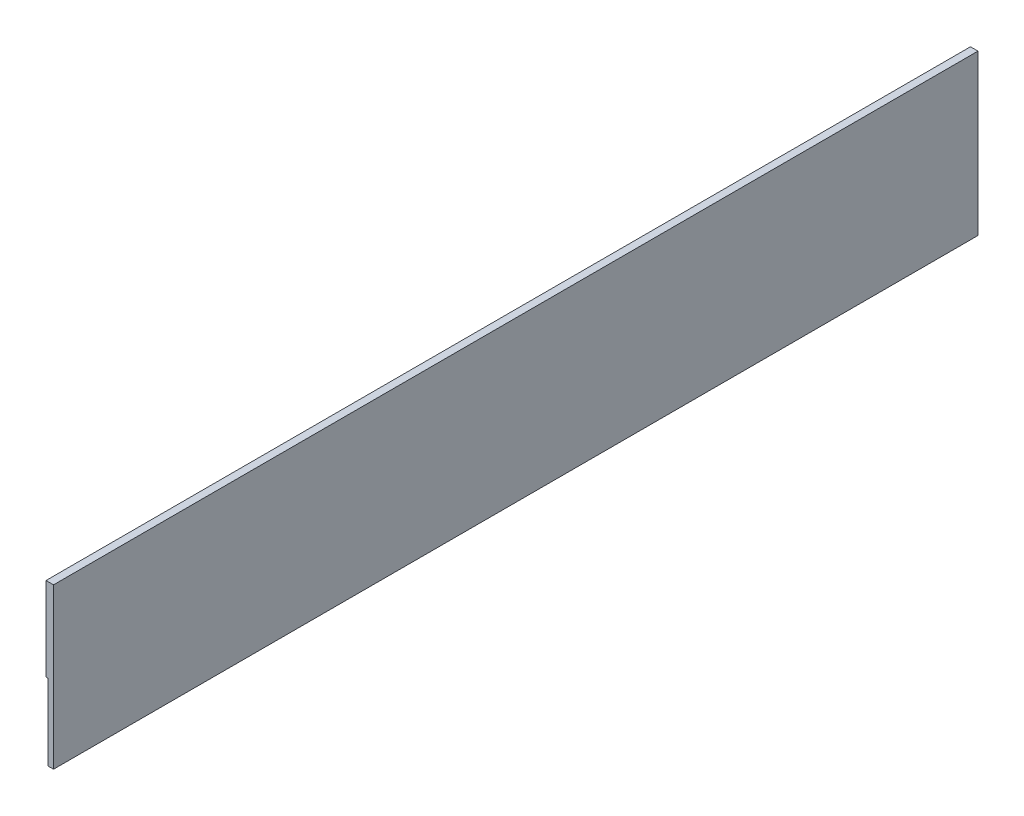
SolidWorks part; units mm, degrees
ref_plane "Front Plane" through (0, 0, 0) normal (0, 0, 1) x (1, 0, 0)
ref_plane "Top Plane" through (0, 0, 0) normal (0, 1, 0) x (1, 0, 0)
ref_plane "Right Plane" through (0, 0, 0) normal (1, 0, 0) x (0, 0, -1)
sketch "Sketch1" plane through (0, 0, 0) normal (1, 0, 0) x (0, 0, -1)
  line L1 (0, 0) -> (12496.8, 0)
  line L2 (0, 0) -> (0, 2159)
  line L3 (0, 2159) -> (12496.8, 2159)
  line L4 (12496.8, 0) -> (12496.8, 2159)
  dimension "D1" = 12496.8
  dimension "D2" = 2159
extrude "Boss-Extrude1" add sketch "Sketch1" along normal blind 76.2
sketch "Sketch2" plane through (0, 0, 0) normal (-1, 0, 0) x (0, 0, 1)
  line L0 (-12496.8, 0) -> (-12496.8, 2159) construction
  line L1 (-12496.8, 1028.7) -> (0, 1028.7)
  line L2 (-12496.8, 1028.7) -> (-12496.8, 2159)
  line L3 (-12496.8, 2159) -> (0, 2159)
  line L4 (0, 1028.7) -> (0, 2159)
  line L5 (-2209.8, 0) -> (-12496.8, 0) construction
  dimension "D1" = 1028.7
extrude "Boss-Extrude2" add sketch "Sketch2" along normal blind 25.4
